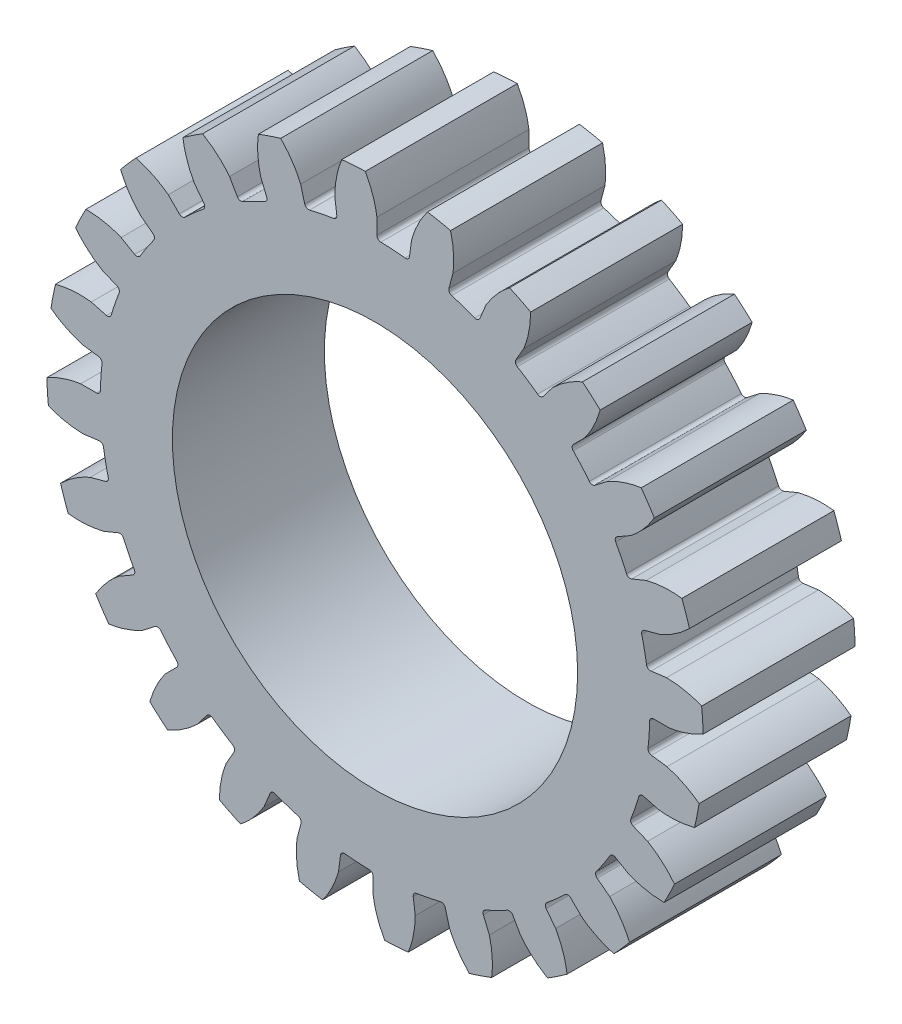
SolidWorks part; units mm, degrees
ref_plane "Front" through (0, 0, 0) normal (0, 0, 1) x (1, 0, 0)
ref_plane "Top" through (0, 0, 0) normal (0, 1, 0) x (1, 0, 0)
ref_plane "Right" through (0, 0, 0) normal (1, 0, 0) x (0, 0, -1)
sketch "Sketch1" plane through (0, 0, 0) normal (0, 0, 1) x (1, 0, 0)
  line L0 (-304.8, 0) -> (304.8, 0) construction
  circle A0 centre (0, 0) radius 10.287
  circle A1 centre (0, 0) radius 9.525 construction
  circle A3 centre (0, 0) radius 8.6066 construction
  dimension "D1" = 0.9184
  dimension "D2" = 1.6804
  dimension "D3" = 0.762
extrude "Boss-Extrude1" add sketch "Sketch1" against normal blind 4.7625
sketch "Sketch2" plane through (0, 0, 0) normal (1, 0, 0) x (0, 0, -1)
  line L0 (4.7625, 0) -> (12.7, 0)
  line L1 (4.7625, 0) -> (4.7625, 8.3344)
  line L2 (4.7625, 8.3344) -> (12.7, 8.3344)
  line L3 (12.7, 8.3344) -> (12.7, 0)
  point P5 (12.7, -8.3344)
sketch "Sketch3" plane through (0, 0, 0) normal (0, 0, 1) x (1, 0, 0)
  line L0 (0, 0) -> (0, 10.287) construction
  line L1 (-2.3089, 8.9279) -> (0, 9.525)
  line L2 (-9.5921, 9.525) -> (9.5921, 9.525) construction
  line L3 (-9.2865, 7.1233) -> (9.2865, 11.9267) construction
  line L4 (-2.3089, 8.9279) -> (0, 0) construction
  line L5 (-5.125, 7.6663) -> (0, 0) construction
  line L6 (-5.125, 7.6663) -> (-0.586, 10.7007) construction
  line L7 (-1.61, 9.08) -> (0, 0) construction
  line L8 (-1.61, 9.08) -> (0.0338, 9.3714) construction
  arc A0 (-2.3089, 8.9279) -> (-5.125, 7.6663) centre (0, 0) ccw
  circle A1 centre (0, 0) radius 9.525 construction
  circle A2 centre (0, 0) radius 9.2216 construction
  arc A3 (-2.3089, 8.9279) -> (-1.61, 9.08) centre (0, 0) cw
  circle A4 centre (0, 0) radius 10.287 construction
  point P6 (0, 9.525)
  dimension "D1" = 2.3849
  dimension "D3" = 5.4598
  dimension "D5" = 1.6694
  dimension "D2" = 3.1003
  dimension "D4" = 0.7155
sketch "Sketch4" plane through (0, 0, 0) normal (0, 0, 1) x (1, 0, 0)
  line L0 (0, 0) -> (0.6216, 9.4843) construction
  line L1 (0.0587, 9.2214) -> (0.0587, 8.6064)
  line L2 (0, 9.525) -> (1.2433, 9.4435) construction
  line L3 (1.1454, 9.1502) -> (1.0651, 8.5405)
  line L4 (0.0587, 8.6064) -> (0, 0) construction
  line L5 (0, 0) -> (0, 10.287) construction
  arc A0 (1.0651, 8.5405) -> (0.0587, 8.6064) centre (0, 0) ccw
  arc A1 (0, 9.525) -> (1.2433, 9.4435) centre (0, 0) cw construction
  circle A2 centre (0, 0) radius 9.525 construction
  circle A3 centre (0, 0) radius 9.2216 construction
  circle A4 centre (0, 0) radius 8.6066 construction
  arc A5 (1.9777, 10.5326) -> (-0.586, 10.7007) centre (0, 0) ccw
  spline S0 degree 2 poles (-0.586, 10.7007) (-0.0544, 10.0259) (0.0587, 9.2214) knots 0 0 0 1 1 1
  spline S1 degree 2 poles (1.9777, 10.5326) (1.3626, 9.933) (1.1454, 9.1502) knots 0 0 0 1 1 1
  dimension "D1" = 1.2468
extrude "Cut-Extrude1" cut sketch "Sketch4" against normal through all
fillet "Fillet1" radius 0.1247 2 edges at (1.0651, 8.5405, -2.3813) (0.0587, 8.6064, -2.3813)
pattern_circular "CirPattern1" count 24 over 360 about axis through (0, 0, -4.7625) along (0, 0, 1) of "Cut-Extrude1", "Fillet1"
sketch "Sketch5" plane through (0, 0, 0) normal (0, 0, 1) x (1, 0, 0)
  circle A0 centre (0, 0) radius 6.35
  circle A1 centre (0, 0) radius 6.35 construction
  dimension "Bore Min" = 12.7
  dimension "Bore Max" = 12.7
extrude "Cut-Extrude2" cut sketch "Sketch5" against normal through all
sketch "Pitch Dia" plane through (0, 0, 0) normal (0, 0, 1) x (1, 0, 0)
  circle A0 centre (0, 0) radius 9.525 construction
  circle A1 centre (0, 0) radius 9.525
sketch "Sketch6" plane through (0, 0, 0) normal (0, 0, 1) x (1, 0, 0)
  line L1 (-5.6127, 5.6127) -> (5.6127, 5.6127)
  line L2 (-5.6127, 5.6127) -> (-5.6127, -5.6127)
  line L3 (-5.6127, -5.6127) -> (5.6127, -5.6127)
  line L4 (5.6127, 5.6127) -> (5.6127, -5.6127)
  circle A0 centre (0, 0) radius 7.9375
  point P7 (0, 0)
  point P8 (0, 0)
  dimension "D1" = 15.875
equation "\"D1@Boss-Extrude1\" = \"Face Wd@Sketch2\""
equation "\"D2@Sketch3\" = \"D1@Sketch3\"*1.3"
equation "\"D3@Sketch3\" = \"D1@Sketch3\"+\"D2@Sketch3\"-.001"
equation "\"D4@Sketch3\" = \"D1@Sketch3\"*.3"
equation "\"D5@Sketch3\" = \"D1@Sketch3\"-\"D4@Sketch3\""
equation "\"D1@Sketch4\" = 1.5708/(\"Number of Teeth@Sketch1\"/\"Ptich Dia@Sketch1\")"
equation "\"D1@Chamfer1\" = \"B Hub Dia@Sketch2\"*.025"
equation "\"D1@CirPattern1\" = \"Number of Teeth@Sketch1\""
equation "\"D1@Fillet1\" = \"D1@Sketch4\"*.1"
equation "\"D1@Fillet2\" = \"OD@Sketch1\"*.01"
equation "\"D1@Sketch1\" = 1.157/(\"Number of Teeth@Sketch1\"/\"Ptich Dia@Sketch1\")"
